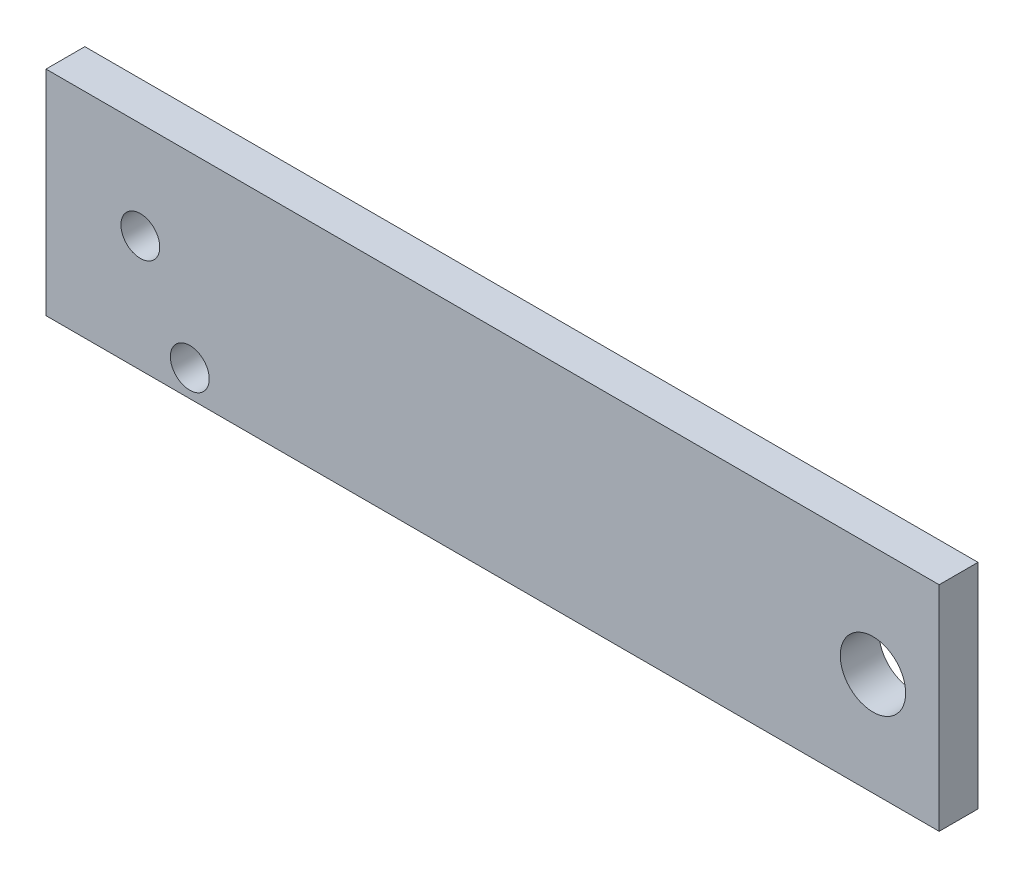
SolidWorks part; units mm, degrees
ref_plane "前视基准面" through (0, 0, 0) normal (0, 0, 1) x (1, 0, 0)
ref_plane "上视基准面" through (0, 0, 0) normal (0, 1, 0) x (1, 0, 0)
ref_plane "右视基准面" through (0, 0, 0) normal (1, 0, 0) x (0, 0, -1)
sketch "草图1" plane through (0, 0, 0) normal (0, 0, 1) x (1, 0, 0)
  line L0 (250, 110) -> (-250, 110)
  line L1 (250, 0) -> (-250, 0)
  line L2 (-250, 110) -> (-250, 0)
  line L3 (250, 110) -> (250, 0)
  circle A0 centre (175.9, 52.9971) radius 16.8443
  circle A1 centre (-175.9468, 13.7778) radius 10
  circle A2 centre (-201.4228, 59.8414) radius 10
extrude "凸台-拉伸1" add sketch "草图1" along normal blind 20
sketch "草图2" plane through (0, 0, 20) normal (0, 0, 1) x (1, 0, 0)
  line L0 (250, 138.8091) -> (210, 138.8091)
  line L2 (210, 138.8091) -> (210, -127.8938)
  dimension "D1" = 40
  dimension "D3" = 266.703
extrude "切除-拉伸1" cut sketch "草图2" against normal through all and the other way through all
